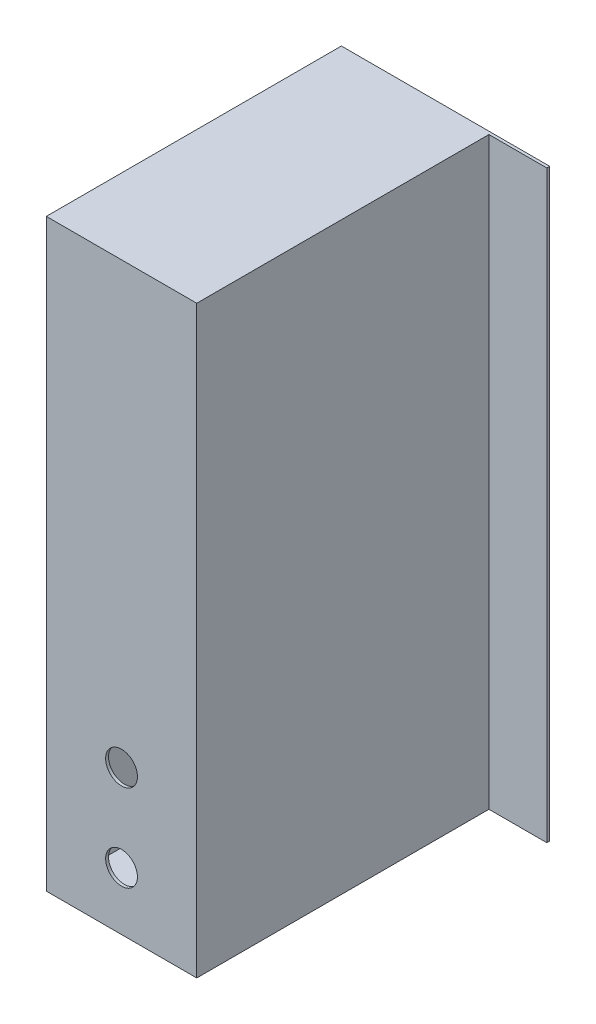
SolidWorks part; units mm, degrees
ref_plane "Plan de face" through (0, 0, 0) normal (0, 0, 1) x (1, 0, 0)
ref_plane "Plan de dessus" through (0, 0, 0) normal (0, 1, 0) x (1, 0, 0)
ref_plane "Plan de droite" through (0, 0, 0) normal (1, 0, 0) x (0, 0, -1)
sketch "Esquisse1" plane through (0, 0, 0) normal (0, 0, 1) x (1, 0, 0)
  line L1 (-26, -101) -> (26, -101)
  line L2 (-26, -101) -> (-26, 101)
  line L3 (-26, 101) -> (26, 101)
  line L4 (26, -101) -> (26, 101)
  line L5 (-26, -101) -> (26, 101) construction
  line L6 (-26, 101) -> (26, -101) construction
  point P0 (0, 0)
  dimension "D1" = 202
  dimension "D2" = 52
extrude "Boss.-Extru.1" add sketch "Esquisse1" along normal blind 102
shell "Coque1" thickness 1
sketch "Esquisse2" plane through (0, 0, 102) normal (0, 0, 1) x (1, 0, 0)
  line L1 (-25, -100) -> (25, -100)
  line L2 (-25, -100) -> (-25, 100)
  line L3 (-25, 100) -> (25, 100)
  line L4 (25, -100) -> (25, 100)
  line L5 (-25, -100) -> (25, 100) construction
  line L6 (-25, 100) -> (25, -100) construction
  point P0 (0, 0)
extrude "Boss.-Extru.2" add sketch "Esquisse2" against normal blind 1
sketch "Esquisse3" plane through (0, 0, 102) normal (0, 0, 1) x (1, 0, 0)
  line L0 (-26, -101) -> (26, -101) construction
  line L1 (-26, 101) -> (-26, -101) construction
  circle A0 centre (0, -81) radius 5.5
  circle A1 centre (0, -51) radius 5.5
  dimension "D1" = 11
  dimension "D2" = 11
  dimension "D3" = 30
  dimension "D4" = 20
  dimension "D5" = 26
  dimension "D6" = 26
extrude "Enlèv. mat.-Extru.1" cut sketch "Esquisse3" against normal blind 1
sketch "Esquisse4" plane through (26, 0, 0) normal (1, 0, 0) x (0, 0, -1)
  line L0 (-102, -101) -> (0, -101) construction
  line L1 (0, 101) -> (-1, 101)
  line L2 (0, 101) -> (0, -101)
  line L3 (0, -101) -> (-1, -101)
  line L4 (-1, 101) -> (-1, -101)
  dimension "D1" = 1
extrude "Boss.-Extru.3" add sketch "Esquisse4" along normal blind 20
